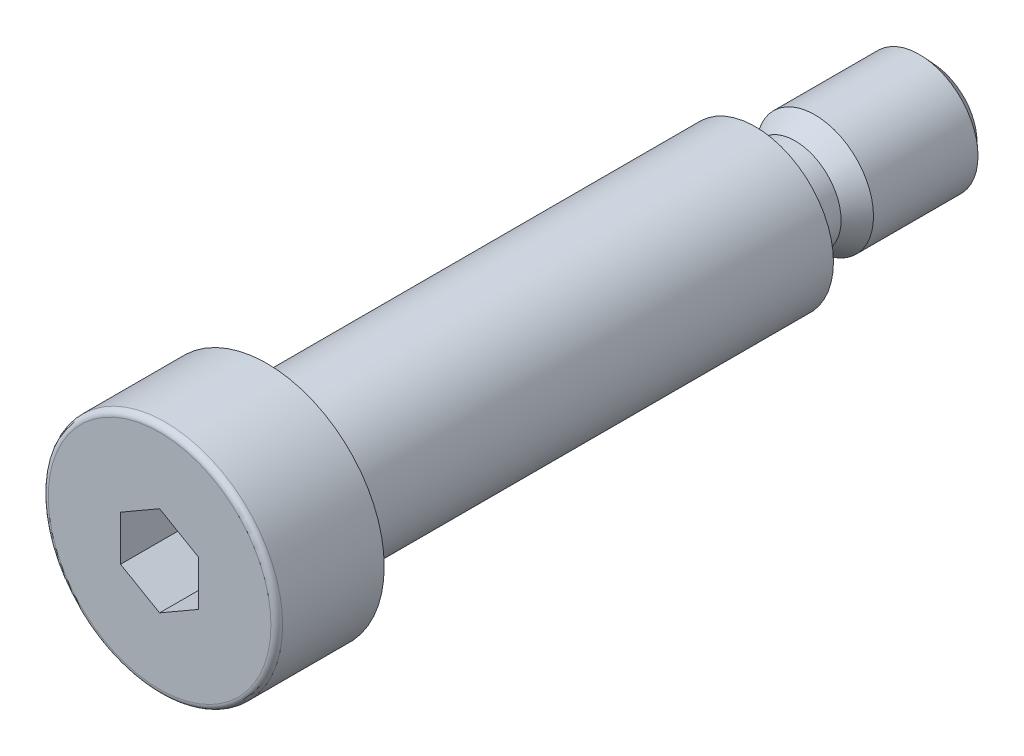
SolidWorks part; units mm, degrees
material "1.0545 (S355N)"
ref_plane "Płaszczyzna przednia" through (0, 0, 0) normal (0, 0, 1) x (1, 0, 0)
ref_plane "Płaszczyzna górna" through (0, 0, 0) normal (0, 1, 0) x (1, 0, 0)
ref_plane "Płaszczyzna prawa" through (0, 0, 0) normal (1, 0, 0) x (0, 0, -1)
sketch "Szkic1" plane through (0, 0, 0) normal (0, 1, 0) x (1, 0, 0)
  line L0 (6, 31.1) -> (4.7, 29.08)
  line L1 (12, -36) -> (-12, -36)
  line L2 (12, -36) -> (12, -25)
  line L3 (12, -25) -> (-12, -25)
  line L4 (-12, -36) -> (-12, -25)
  line L5 (8, -25) -> (-8, -25)
  line L6 (8, -25) -> (8, 25)
  line L7 (8, 25) -> (-8, 25)
  line L8 (-8, -25) -> (-8, 25)
  line L9 (-4.7, 25) -> (4.7, 25)
  line L10 (-4.7, 25) -> (-4.7, 29.08)
  line L11 (-4.7, 29.08) -> (4.7, 29.08)
  line L12 (4.7, 25) -> (4.7, 29.08)
  line L13 (6, 31.1) -> (6, 41.8)
  line L14 (6, 41.8) -> (4.7, 43)
  line L15 (4.7, 43) -> (-4.7, 43)
  line L16 (-4.7, 43) -> (-6, 41.8)
  line L17 (-6, 41.8) -> (-6, 31.1)
  line L18 (-6, 31.1) -> (-4.7, 29.08)
  line L19 (6, 31.1) -> (-6, 31.1) construction
  line L20 (6, 41.8) -> (-6, 41.8) construction
  line L21 (0, -19.9356) -> (0, 25.6583) construction
  line L22 (0, -36) -> (0, 43)
  point P4 (0, -25)
  point P14 (0, -25)
  point P15 (0, 25)
  point P16 (0, 25)
  point P17 (-8, 0)
  point P23 (0, 31.1)
  point P25 (0, 43)
  point P26 (0, 29.08)
  point P27 (0, 41.8)
  dimension "D1" = 24
  dimension "D2" = 11
  dimension "D3" = 16
  dimension "l1" = 50
  dimension "D5" = 9.4
  dimension "D6" = 18
  dimension "D7" = 12
  dimension "D8" = 9.4
  dimension "D9" = 1.2
  dimension "D10" = 2.02
  dimension "D11" = 10.7
revolve "Obrót1" add sketch "Szkic1" angle 360 about L22
sketch "Szkic2" plane through (0, 0, 36) normal (0, 0, 1) x (1, 0, 0)
  line L1 (4, 2.3094) -> (0, 4.6188)
  line L2 (0, 4.6188) -> (-4, 2.3094)
  line L3 (-4, 2.3094) -> (-4, -2.3094)
  line L4 (-4, -2.3094) -> (0, -4.6188)
  line L5 (0, -4.6188) -> (4, -2.3094)
  line L6 (4, -2.3094) -> (4, 2.3094)
  circle A0 centre (0, 0) radius 4 construction
  dimension "D1" = 8
extrude "Wytnij-wyciągnięcie1" cut sketch "Szkic2" against normal blind 6.6
fillet "Zaokrąglenie1" radius 0.6 1 edges at (12, 0, 36)
